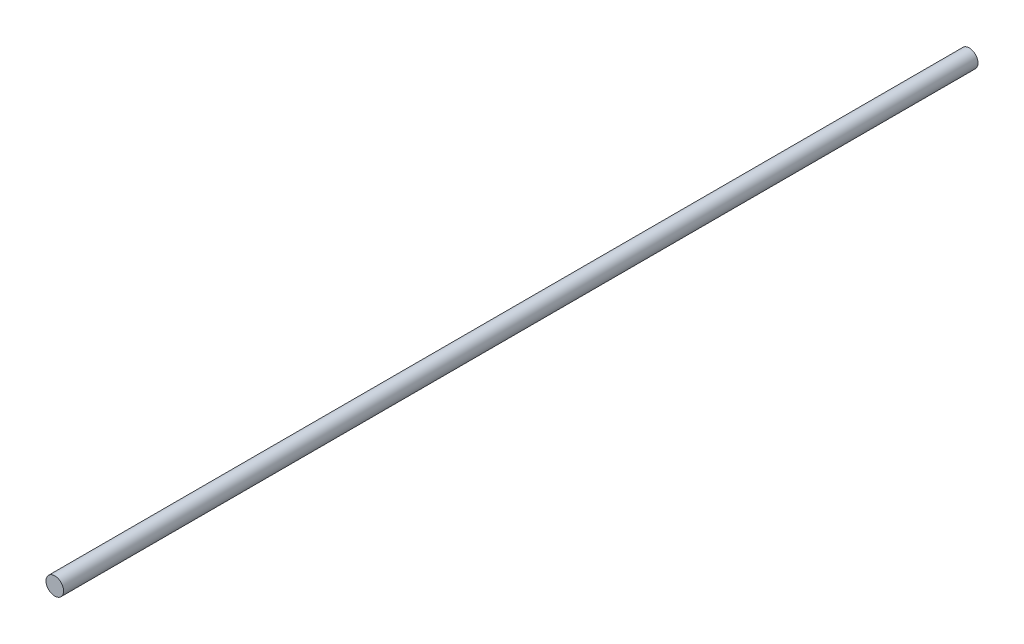
SolidWorks part; units mm, degrees
material "AISI 1015 Steel, Cold Drawn (SS)"
ref_plane "Front Plane" through (0, 0, 0) normal (0, 0, 1) x (1, 0, 0)
ref_plane "Top Plane" through (0, 0, 0) normal (0, 1, 0) x (1, 0, 0)
ref_plane "Right Plane" through (0, 0, 0) normal (1, 0, 0) x (0, 0, -1)
sketch "Sketch1" plane through (0, 0, 0) normal (0, 0, 1) x (1, 0, 0)
  circle A0 centre (-177.8, -95.25) radius 6.35
  dimension "D1" = 12.7
extrude "Boss-Extrude1" add sketch "Sketch1" along normal offset from surface (660.4 mm away) 127
